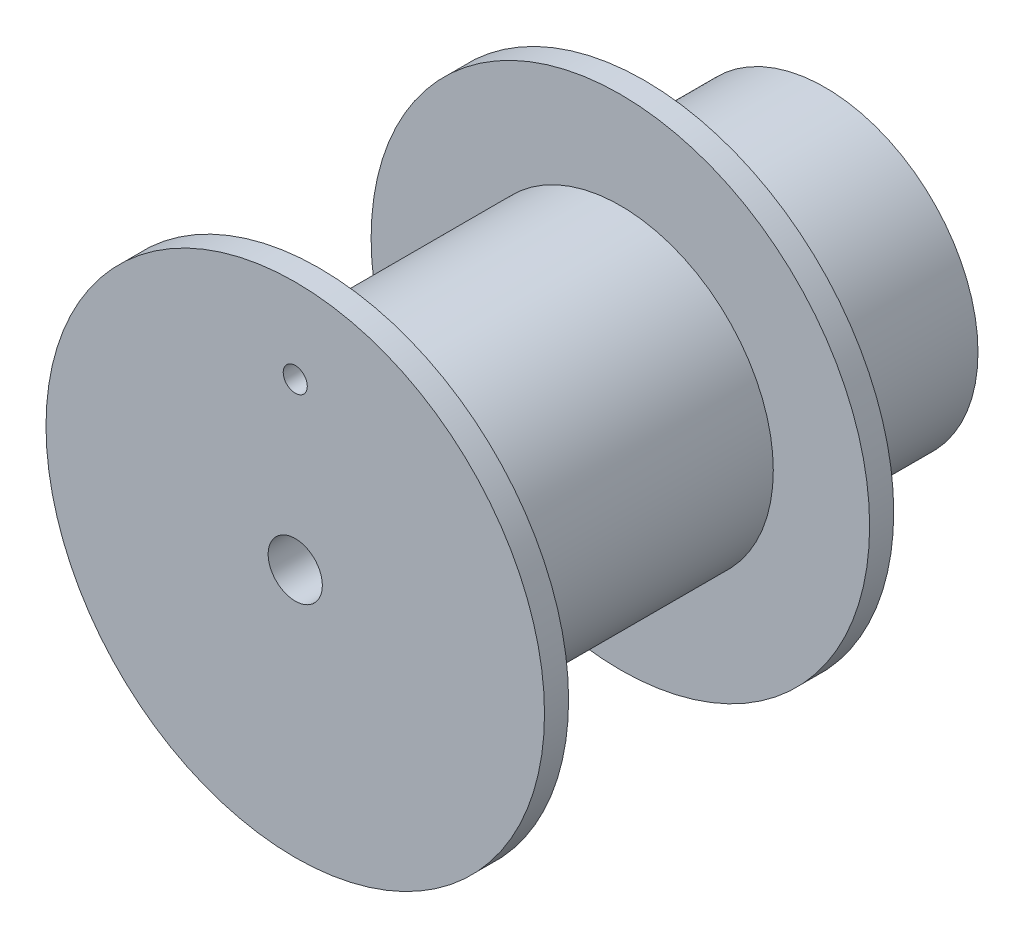
SolidWorks part; units mm, degrees
ref_plane "Front Plane" through (0, 0, 0) normal (0, 0, 1) x (1, 0, 0)
ref_plane "Top Plane" through (0, 0, 0) normal (0, 1, 0) x (1, 0, 0)
ref_plane "Right Plane" through (0, 0, 0) normal (1, 0, 0) x (0, 0, -1)
sketch "Sketch1" plane through (0, 0, 0) normal (0, 0, 1) x (1, 0, 0)
  line L0 (0, 0) -> (0, 10.5) construction
  line L2 (-2.7, 6.7285) -> (-2.7, 10.5)
  line L3 (-2.7, 10.5) -> (2.7, 10.5)
  line L4 (2.7, 6.7285) -> (2.7, 10.5)
  arc A0 (-2.7, 6.7285) -> (2.7, 6.7285) centre (0, 0) ccw
  circle A1 centre (0, 0) radius 12.7
  dimension "D1" = 14.5
  dimension "D4" = 25.4
  dimension "D2" = 5.4
  dimension "D3" = 10.5
extrude "Boss-Extrude1" add sketch "Sketch1" along normal blind 28
ref_plane "Plane1" through (0, 0, 15) normal (0, 0, -1) x (-1, 0, 0)
sketch "Sketch3" plane through (0, 0, 15) normal (0, 0, -1) x (-1, 0, 0)
  circle A0 centre (0, 0) radius 12.7 construction
  circle A1 centre (0, 0) radius 12.7
  circle A2 centre (0, 0) radius 20.7
  dimension "D1" = 8
extrude "Boss-Extrude2" add sketch "Sketch3" against normal blind 2
sketch "Sketch4" plane through (0, 0, 28) normal (0, 0, 1) x (1, 0, 0)
  circle A0 centre (0, 0) radius 12.7 construction
  circle A1 centre (0, 0) radius 12.7
  circle A2 centre (0, 0) radius 2.25
  dimension "D1" = 4.5
extrude "Boss-Extrude3" add sketch "Sketch4" along normal blind 14
sketch "Sketch5" plane through (0, 0, 42) normal (0, 0, 1) x (1, 0, 0)
  circle A0 centre (0, 0) radius 2.25 construction
  circle A1 centre (0, 0) radius 20.7 construction
  circle A2 centre (0, 0) radius 2.25
  circle A3 centre (0, 0) radius 20.7
  circle A4 centre (0, 0) radius 12.7 construction
  circle A5 centre (0, 0) radius 12.7 construction
  circle A6 centre (0, 13.7) radius 1
  dimension "D1" = 2
extrude "Boss-Extrude4" add sketch "Sketch5" along normal blind 2
